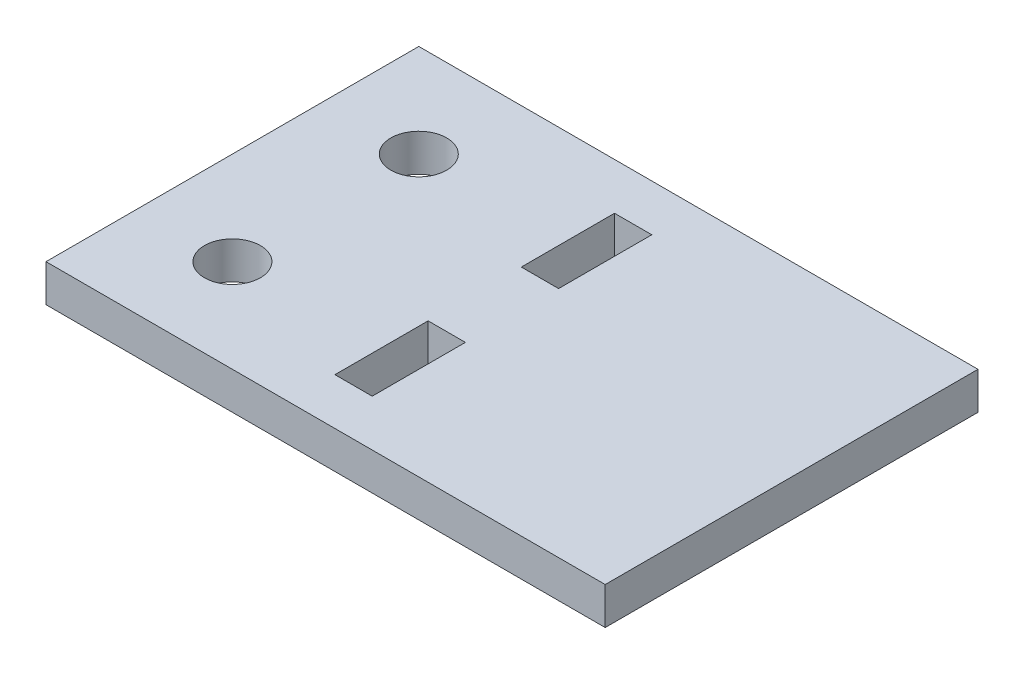
SolidWorks part; units mm, degrees
ref_plane "Front Plane" through (0, 0, 0) normal (0, 0, 1) x (1, 0, 0)
ref_plane "Top Plane" through (0, 0, 0) normal (0, 1, 0) x (1, 0, 0)
ref_plane "Right Plane" through (0, 0, 0) normal (1, 0, 0) x (0, 0, -1)
sketch "Sketch1" plane through (0, 0, 0) normal (0, 1, 0) x (1, 0, 0)
  line L0 (-2, 13.2967) -> (-2, -16.3004) construction
  line L1 (-15, 10) -> (15, 10)
  line L2 (-15, 10) -> (-15, -10)
  line L3 (-15, -10) -> (15, -10)
  line L4 (15, 10) -> (15, -10)
  line L5 (-15, 10) -> (15, -10) construction
  line L6 (-15, -10) -> (15, 10) construction
  line L7 (-2, 7.5) -> (-2, 2.5)
  line L8 (-2, 7.5) -> (0, 7.5)
  line L9 (-2, 2.5) -> (0, 2.5)
  line L10 (0, 7.5) -> (0, 2.5)
  line L11 (-2, -2.5) -> (-2, -7.5)
  line L12 (-2, -2.5) -> (0, -2.5)
  line L13 (-2, -7.5) -> (0, -7.5)
  line L14 (0, -2.5) -> (0, -7.5)
  point P0 (0, 0)
  point P8 (0, 5)
  point P15 (0, -5)
  dimension "D1" = 20
  dimension "D2" = 30
  dimension "D3" = 17
  dimension "D4" = 2
  dimension "D5" = 2
  dimension "D6" = 5
  dimension "D7" = 5
  dimension "D8" = 5
  dimension "D9" = 5
extrude "Boss-Extrude1" add sketch "Sketch1" along normal blind 2
sketch "Sketch2" plane through (0, 2, 0) normal (0, 1, 0) x (1, 0, 0)
  line L0 (-10, 12.4144) -> (-10, -13.471) construction
  line L1 (-15, 10) -> (-15, -10) construction
  line L2 (15, 10) -> (-15, 10) construction
  line L3 (-15, -10) -> (15, -10) construction
  circle A0 centre (-10, 5) radius 1.5
  circle A1 centre (-10, -5) radius 1.5
  dimension "D2" = 3
  dimension "D3" = 3
  dimension "D1" = 5
  dimension "D4" = 5
  dimension "D5" = 5
extrude "Cut-Extrude1" cut sketch "Sketch2" against normal blind 10
